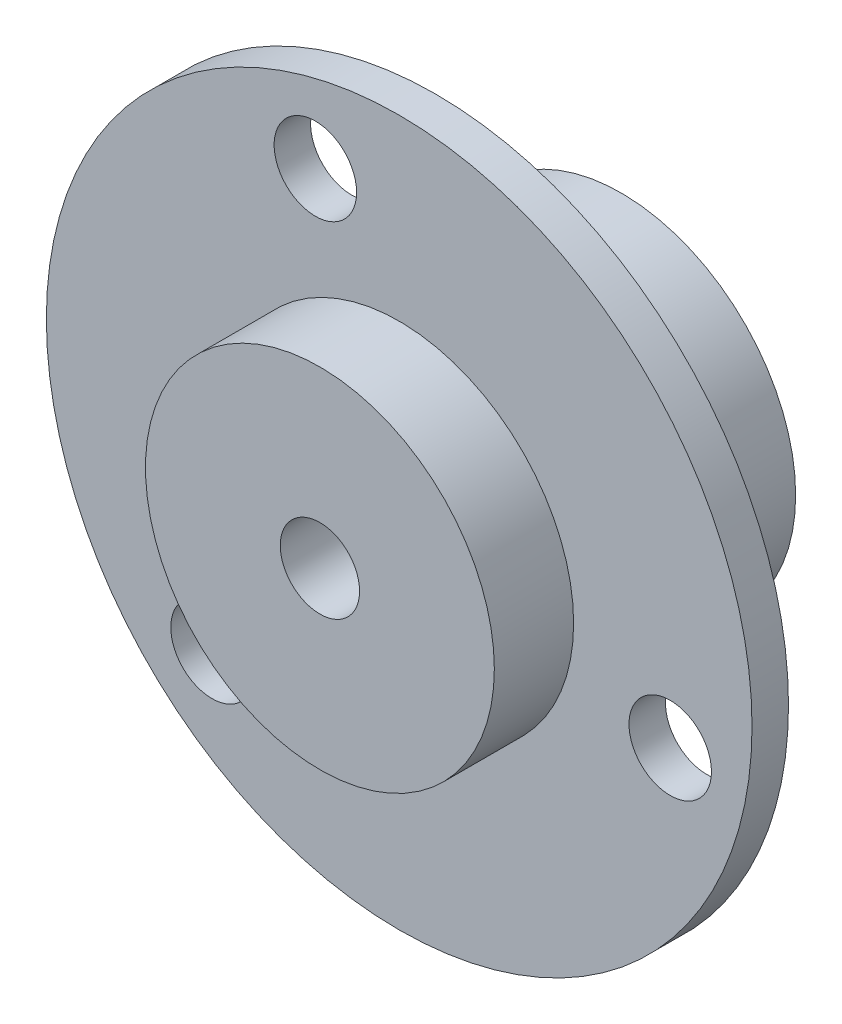
SolidWorks part; units mm, degrees
ref_plane "前视基准面" through (0, 0, 0) normal (0, 0, 1) x (1, 0, 0)
ref_plane "上视基准面" through (0, 0, 0) normal (0, 1, 0) x (1, 0, 0)
ref_plane "右视基准面" through (0, 0, 0) normal (1, 0, 0) x (0, 0, -1)
other "Configuration Table"
sketch "草图1" plane through (0, 0, 0) normal (0, 0, 1) x (1, 0, 0)
  circle A0 centre (-102.0095, 21.1397) radius 22.25
  circle A1 centre (-102.0095, 21.1397) radius 17.5 construction
  circle A2 centre (-84.9189, 17.3766) radius 2.6
  circle A3 centre (-102.0095, 21.1397) radius 2.5
  circle A4 centre (-113.8138, 8.2204) radius 2.6
  circle A5 centre (-107.2958, 37.8222) radius 2.6
  point P12 (-102.0095, 21.1397)
  dimension "D1" = 44.5
  dimension "D2" = 35
  dimension "D3" = 5.2
  dimension "D4" = 5
  dimension "D5" = 3
extrude "凸台-拉伸1" add sketch "草图1" along normal blind 2.3
sketch "草图2" plane through (0, 0, 2.3) normal (0, 0, 1) x (1, 0, 0)
  circle A0 centre (-102.0095, 21.1397) radius 11
  circle A1 centre (-102.0095, 21.1397) radius 2.5 construction
  circle A2 centre (-102.0095, 21.1397) radius 2.5
  dimension "D1" = 22
extrude "凸台-拉伸2" add sketch "草图2" along normal blind 5 and the other way blind 14
